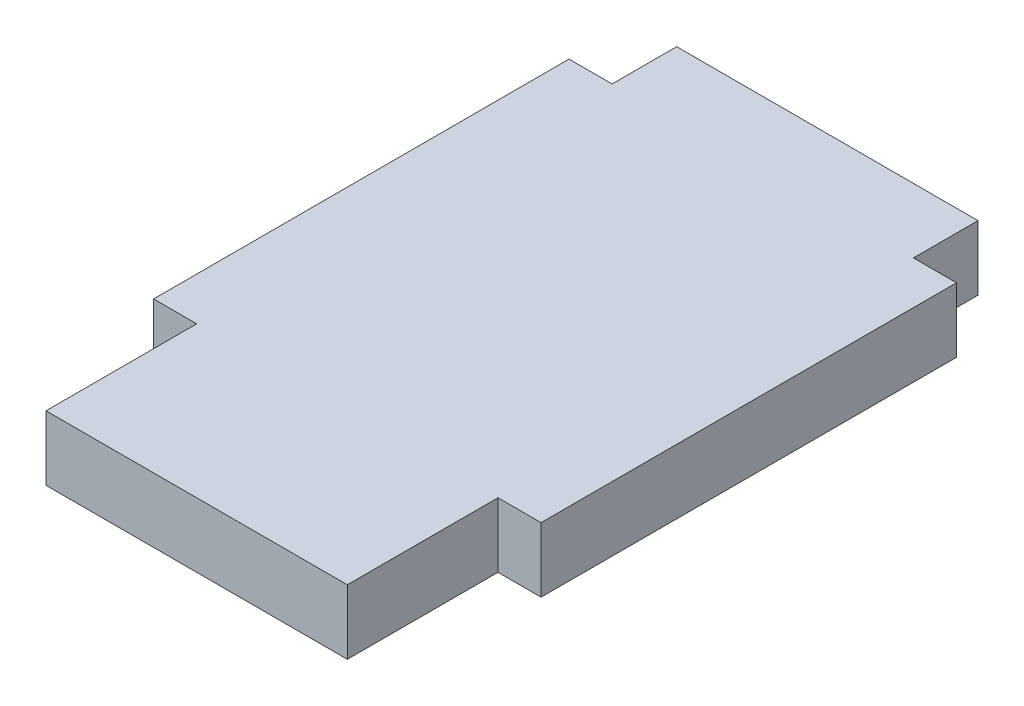
SolidWorks part; units mm, degrees
ref_plane "Спереди" through (0, 0, 0) normal (0, 0, 1) x (1, 0, 0)
ref_plane "Сверху" through (0, 0, 0) normal (0, 1, 0) x (1, 0, 0)
ref_plane "Справа" through (0, 0, 0) normal (1, 0, 0) x (0, 0, -1)
other "Configuration Table"
sketch "Эскиз1" plane through (0, 0, 0) normal (0, 1, 0) x (1, 0, 0)
  line L2 (-9, -10.4345) -> (-9, 8.8655)
  line L3 (-7, 11.8655) -> (7, 11.8655)
  line L4 (9, -10.4345) -> (9, 8.8655)
  line L7 (-7, 11.8655) -> (-7, 8.8655)
  line L8 (-7, 8.8655) -> (-9, 8.8655)
  line L9 (7, 11.8655) -> (7, 8.8655)
  line L10 (7, 8.8655) -> (9, 8.8655)
  line L12 (7, -10.4345) -> (9, -10.4345)
  line L13 (7, -13.4345) -> (7, -10.4345)
  line L14 (-7, -10.4345) -> (-9, -10.4345)
  line L15 (-7, -13.4345) -> (-7, -10.4345)
  line L17 (-7, -13.4345) -> (7, -13.4345)
  point P0 (-8, -10.4345)
  point P9 (0, 11.8655)
  point P21 (0, -25)
  dimension "D1" = 25.3
  dimension "D2" = 3
  dimension "D3" = 14
  dimension "D4" = 3
  dimension "D5" = 3
  dimension "D6" = 3
extrude "Бобышка-Вытянуть1" add sketch "Эскиз1" along normal blind 3 contours L2 L8 L7 L3 L9 L10 L4 L12 L13 L17 L15 L14
sketch "Эскиз3" plane through (0, 0, 13.4345) normal (0, 0, 1) x (1, 0, 0)
  line L1 (-7, 3) -> (7, 3)
  line L2 (-7, 3) -> (-7, 0)
  line L3 (-7, 0) -> (7, 0)
  line L4 (7, 3) -> (7, 0)
extrude "Бобышка-Вытянуть2" add sketch "Эскиз3" along normal blind 4
